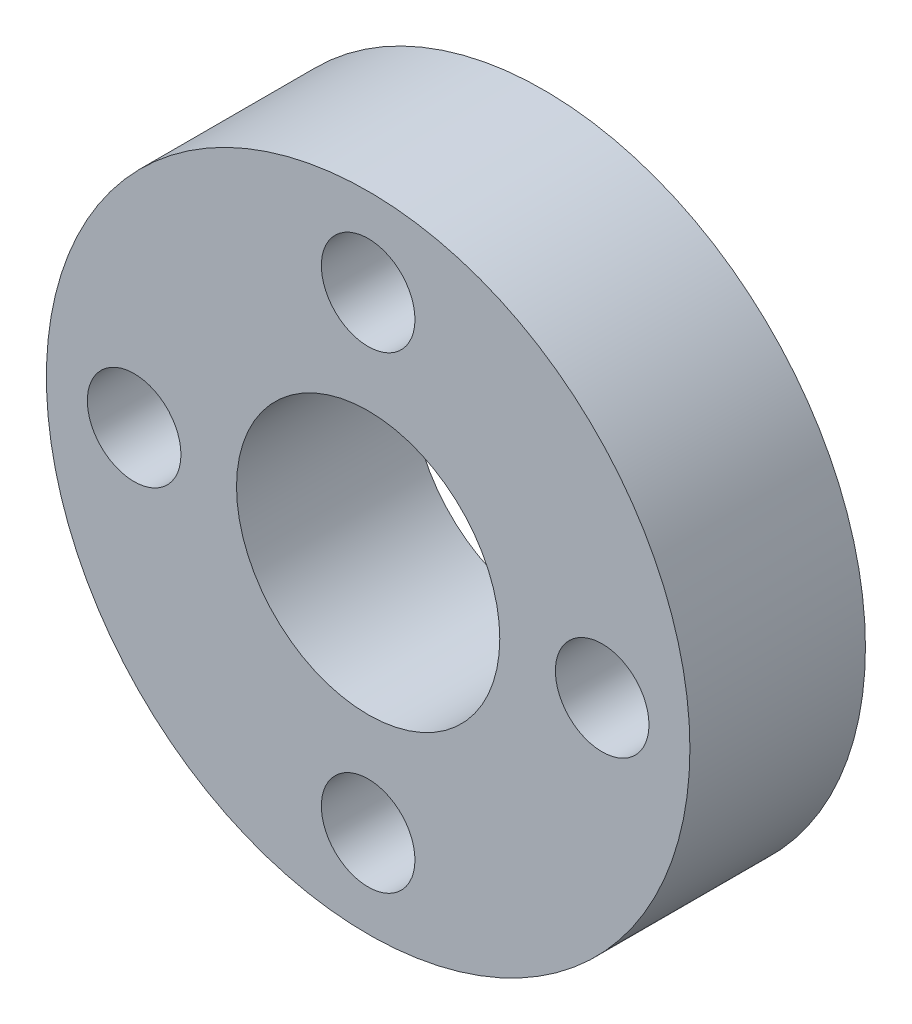
SolidWorks part; units mm, degrees
ref_plane "Front" through (0, 0, 0) normal (0, 0, 1) x (1, 0, 0)
ref_plane "Top" through (0, 0, 0) normal (0, 1, 0) x (1, 0, 0)
ref_plane "Right" through (0, 0, 0) normal (1, 0, 0) x (0, 0, -1)
sketch "Sketch1" plane through (0, 0, 0) normal (0, 0, 1) x (1, 0, 0)
  line L0 (0, 0) -> (8, 0) construction
  line L1 (0, 0) -> (-8, 0) construction
  line L2 (0, 0) -> (0, 8) construction
  line L3 (0, 0) -> (0, -8) construction
  circle A0 centre (0, 0) radius 11
  circle A1 centre (0, 0) radius 4.5
  circle A2 centre (8, 0) radius 1.6
  circle A3 centre (0, 8) radius 1.6
  circle A4 centre (-8, 0) radius 1.6
  circle A5 centre (0, -8) radius 1.6
  dimension "D1" = 9
  dimension "D2" = 22
  dimension "D3" = 3.2
  dimension "D4" = 8
extrude "Boss-Extrude1" add sketch "Sketch1" along normal blind 6
